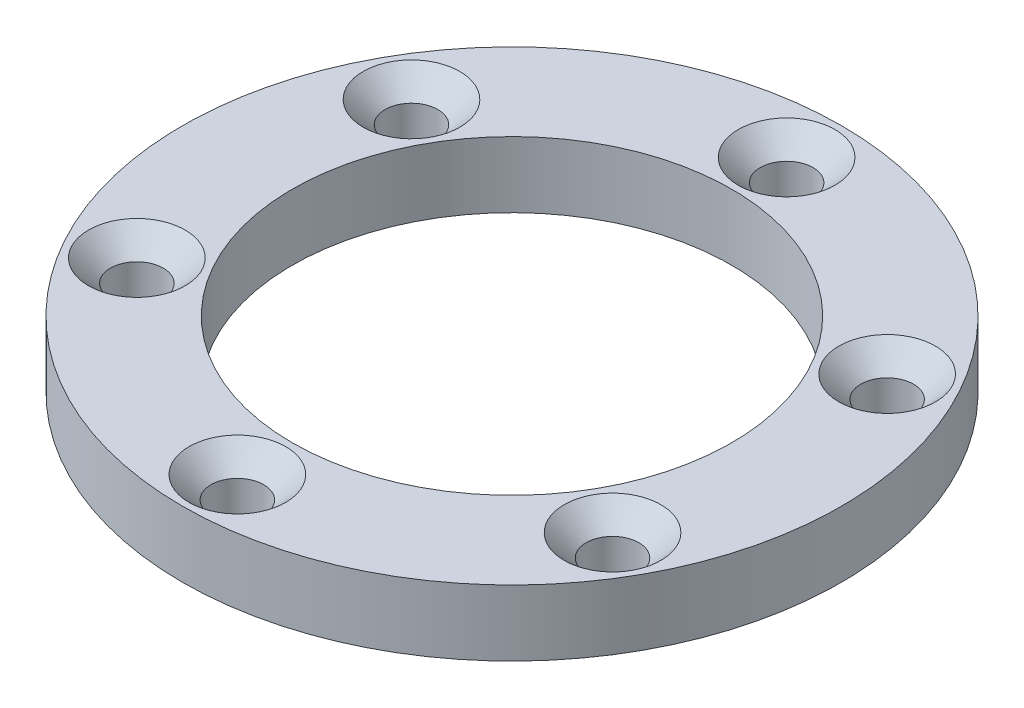
SolidWorks part; units mm, degrees
ref_plane "Front Plane" through (0, 0, 0) normal (0, 0, 1) x (1, 0, 0)
ref_plane "Top Plane" through (0, 0, 0) normal (0, 1, 0) x (1, 0, 0)
ref_plane "Right Plane" through (0, 0, 0) normal (1, 0, 0) x (0, 0, -1)
sketch "Sketch1" plane through (0, 0, 0) normal (0, 1, 0) x (1, 0, 0)
  circle A0 centre (0, 0) radius 10
  circle A1 centre (0, 0) radius 15
  dimension "D1" = 30
  dimension "D2" = 20
extrude "Boss-Extrude1" add sketch "Sketch1" along normal mid plane 3
sketch "Sketch2" plane through (0, 1.5, 0) normal (0, 1, 0) x (1, 0, 0)
  circle A0 centre (0, 0) radius 12.5 construction
  dimension "D1" = 25
sketch "Sketch4" plane through (0, 1.5, 0) normal (0, 1, 0) x (1, 0, 0)
  line L0 (0, 0) -> (0, 12.5) construction
  circle A0 centre (0, 0) radius 12.5 construction
hole_wizard "CSK for M2 Flat Head Machine Screw1" positions "3DSketch2" profile "Sketch6" countersink size "M2" standard "ANSI Metric" end condition through all
sketch3d "3DSketch2"
  point P0 (0, 1.5, -12.5)
sketch "Sketch6" plane through (0, 1.5, -12.5) normal (1, 0, 0) x (0, 0, 1)
  line L0 (0, 0) -> (0, 3)
  line L1 (0, 3) -> (1.2, 3)
  line L2 (1.2, 3) -> (1.2, 1)
  line L3 (1.2, 1) -> (2.2, 0)
  line L5 (2.2, 0) -> (0, 0)
  line L6 (-1.2, 1) -> (-2.2, 0) construction
  line L11 (0, -6.35) -> (0, 107.95) construction
  dimension "Thru Hole Dia." = 2.4
  dimension "Thru Hole Depth" = 3
  dimension "Near C'Sink Dia." = 4.4
  dimension "Near C'Sink Angle" = 90
pattern_circular "CirPattern1" count 6 over 360 about axis through (0, 0, 0) along (0, 1, 0) of "CSK for M2 Flat Head Machine Screw1"
